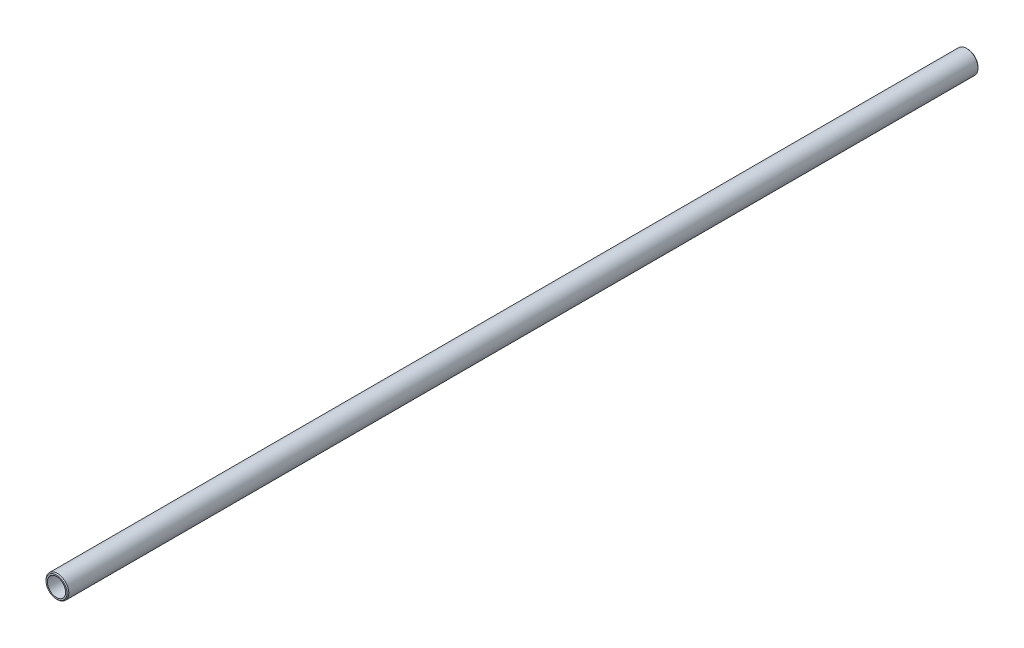
SolidWorks part; units mm, degrees
material "1060 Alloy"
ref_plane "Front Plane" through (0, 0, 0) normal (0, 0, 1) x (1, 0, 0)
ref_plane "Top Plane" through (0, 0, 0) normal (0, 1, 0) x (1, 0, 0)
ref_plane "Right Plane" through (0, 0, 0) normal (1, 0, 0) x (0, 0, -1)
sketch "Sketch1" plane through (0, 0, 0) normal (0, 0, 1) x (1, 0, 0)
  circle A0 centre (0, 0) radius 5
  circle A1 centre (0, 0) radius 4
  dimension "1" = 10
  dimension "D2" = 8
extrude "body" add sketch "Sketch1" along normal blind 400
chamfer "end_chamfers" distance 0.4 angle 45 2 edges at (5, 0, 0) (5, 0, 400)
